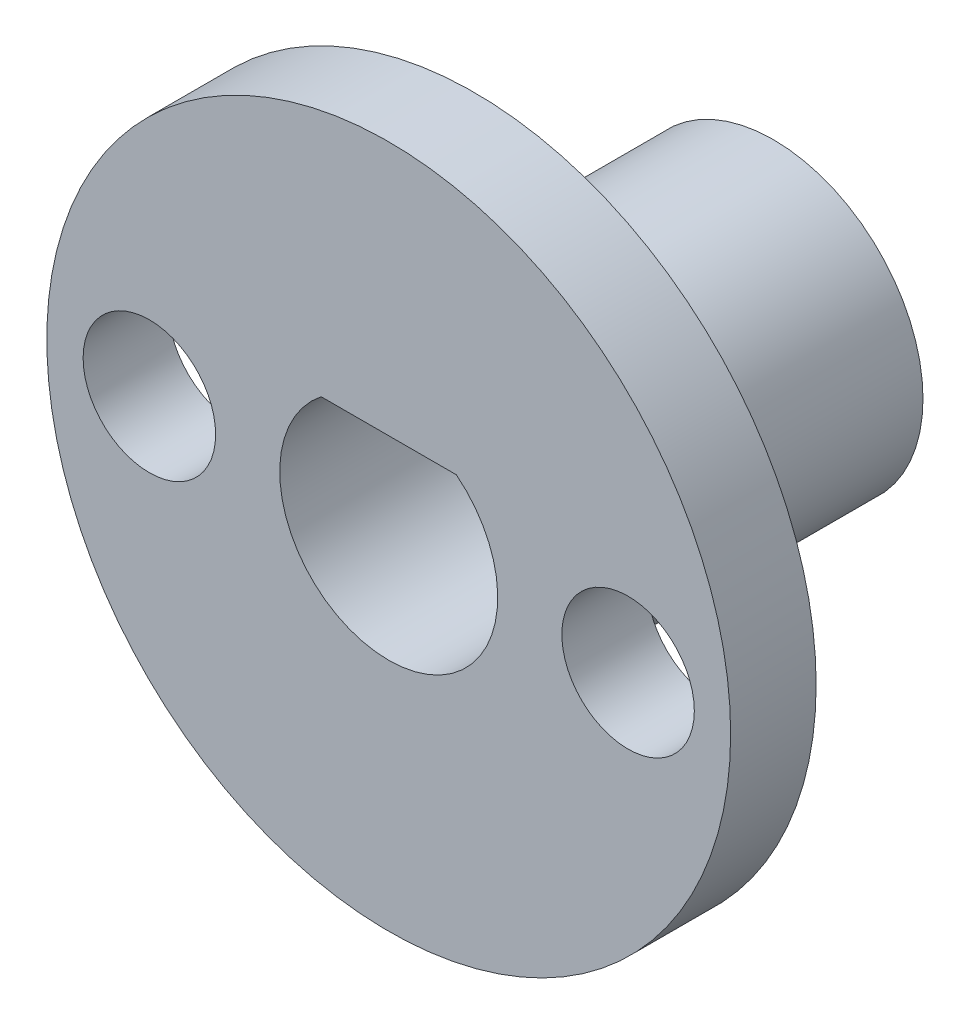
SolidWorks part; units mm, degrees
ref_plane "前视基准面" through (0, 0, 0) normal (0, 0, 1) x (1, 0, 0)
ref_plane "上视基准面" through (0, 0, 0) normal (0, 1, 0) x (1, 0, 0)
ref_plane "右视基准面" through (0, 0, 0) normal (1, 0, 0) x (0, 0, -1)
sketch "草图1" plane through (0, 0, 0) normal (0, 0, 1) x (1, 0, 0)
  line L0 (-1.5819, 2) -> (1.5819, 2)
  circle A0 centre (0, 0) radius 3.5
  arc A1 (-1.5819, 2) -> (1.5819, 2) centre (0, 0) ccw
  point P8 (0.6963, -2.4071)
  dimension "D1" = 7
  dimension "D2" = 5.1
  dimension "D3" = 2
extrude "凸台-拉伸1" add sketch "草图1" along normal blind 6 and the other way blind 3 contours A0
sketch "草图2" plane through (0, 0, -3) normal (0, 0, -1) x (-1, 0, 0)
  line L0 (1.5819, 2) -> (-1.5819, 2) construction
  line L1 (1.5819, 2) -> (-1.5819, 2)
  arc A0 (-1.5819, 2) -> (1.5819, 2) centre (0, 0) ccw construction
  arc A1 (-1.5819, 2) -> (1.5819, 2) centre (0, 0) ccw
extrude "切除-拉伸1" cut sketch "草图2" against normal through all and the other way through all
sketch "草图3" plane through (0, 0, 6) normal (0, 0, 1) x (1, 0, 0)
  circle A0 centre (0, -0.0432) radius 8
  dimension "D1" = 16
extrude "凸台-拉伸2" add sketch "草图3" against normal blind 2 contours A0
sketch "草图4" plane through (0, 0, 6) normal (0, 0, 1) x (1, 0, 0)
  line L0 (-1.5819, 2) -> (1.5819, 2) construction
  line L1 (-1.5819, 2) -> (1.5819, 2)
  arc A0 (-1.5819, 2) -> (1.5819, 2) centre (0, 0) ccw construction
  arc A1 (-1.5819, 2) -> (1.5819, 2) centre (0, 0) ccw
extrude "切除-拉伸2" cut sketch "草图4" against normal through all
sketch "草图5" plane through (0, 0, 6) normal (0, 0, 1) x (1, 0, 0)
  line L0 (0, 0) -> (0, 5.9568) construction
  circle A0 centre (5.6, 0) radius 1.55
  circle A2 centre (-5.6, 0) radius 1.55
  dimension "D1" = 3.1
  dimension "D2" = 5.6
extrude "切除-拉伸3" cut sketch "草图5" against normal blind 2.5
